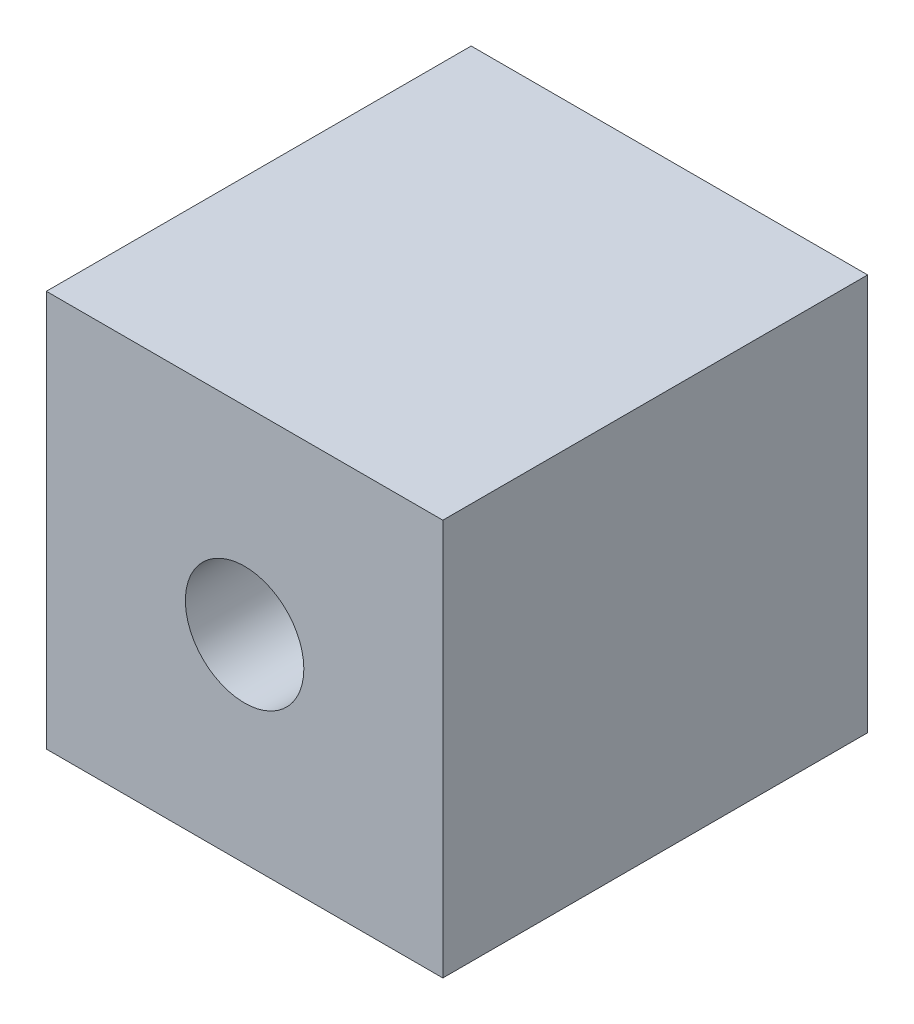
SolidWorks part; units mm, degrees
ref_plane "Front" through (0, 0, 0) normal (0, 0, 1) x (1, 0, 0)
ref_plane "Top" through (0, 0, 0) normal (0, 1, 0) x (1, 0, 0)
ref_plane "Right" through (0, 0, 0) normal (1, 0, 0) x (0, 0, -1)
other "Configuration Table"
sketch "Sketch1" plane through (0, 0, 0) normal (0, 0, 1) x (1, 0, 0)
  line L1 (0, 0) -> (17.78, 0)
  line L2 (0, 0) -> (0, 17.78)
  line L3 (0, 17.78) -> (17.78, 17.78)
  line L4 (17.78, 0) -> (17.78, 17.78)
  dimension "D1" = 17.78
  dimension "D2" = 17.78
extrude "Extrude1" add sketch "Sketch1" against normal blind 19.05
sketch "Sketch2" plane through (0, 0, 0) normal (0, 0, 1) x (1, 0, 0)
  line L0 (0, 17.78) -> (0, 0) construction
  line L1 (17.78, 17.78) -> (0, 17.78) construction
  circle A0 centre (8.89, 8.89) radius 2.6568
  dimension "D3" = 5.3137
  dimension "D1" = 8.89
  dimension "D2" = 8.89
extrude "Cut-Extrude1" cut sketch "Sketch2" against normal blind 14
